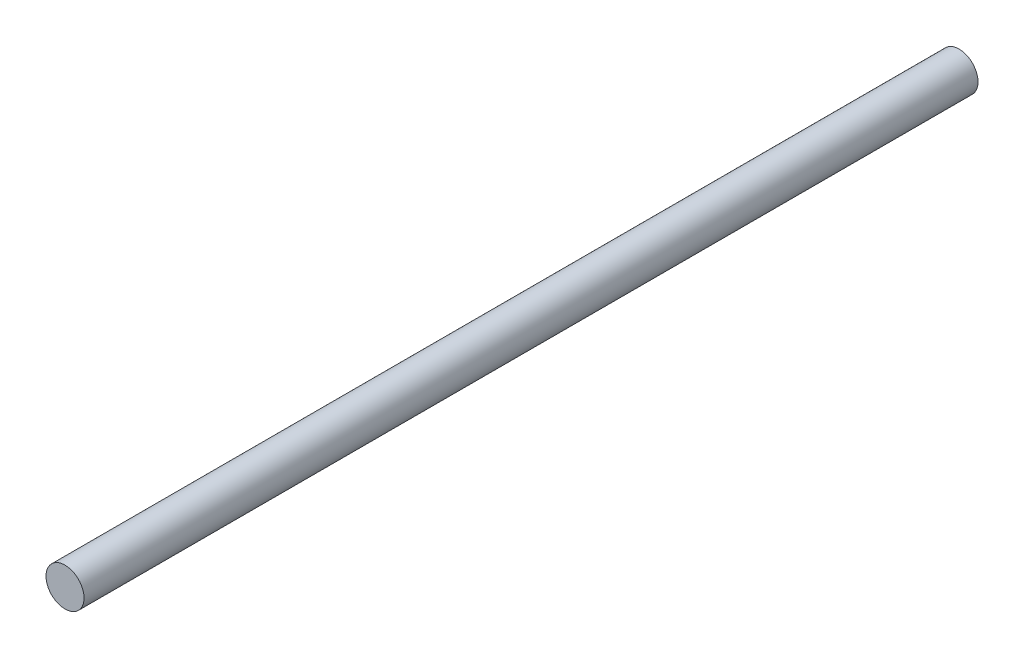
SolidWorks part; units mm, degrees
ref_plane "Front Plane" through (0, 0, 0) normal (0, 0, 1) x (1, 0, 0)
ref_plane "Top Plane" through (0, 0, 0) normal (0, 1, 0) x (1, 0, 0)
ref_plane "Right Plane" through (0, 0, 0) normal (1, 0, 0) x (0, 0, -1)
sketch "Sketch1" plane through (0, 0, 0) normal (0, 0, 1) x (1, 0, 0)
  circle A0 centre (0, 0) radius 10
extrude "Boss-Extrude1" add sketch "Sketch1" along normal blind 470
